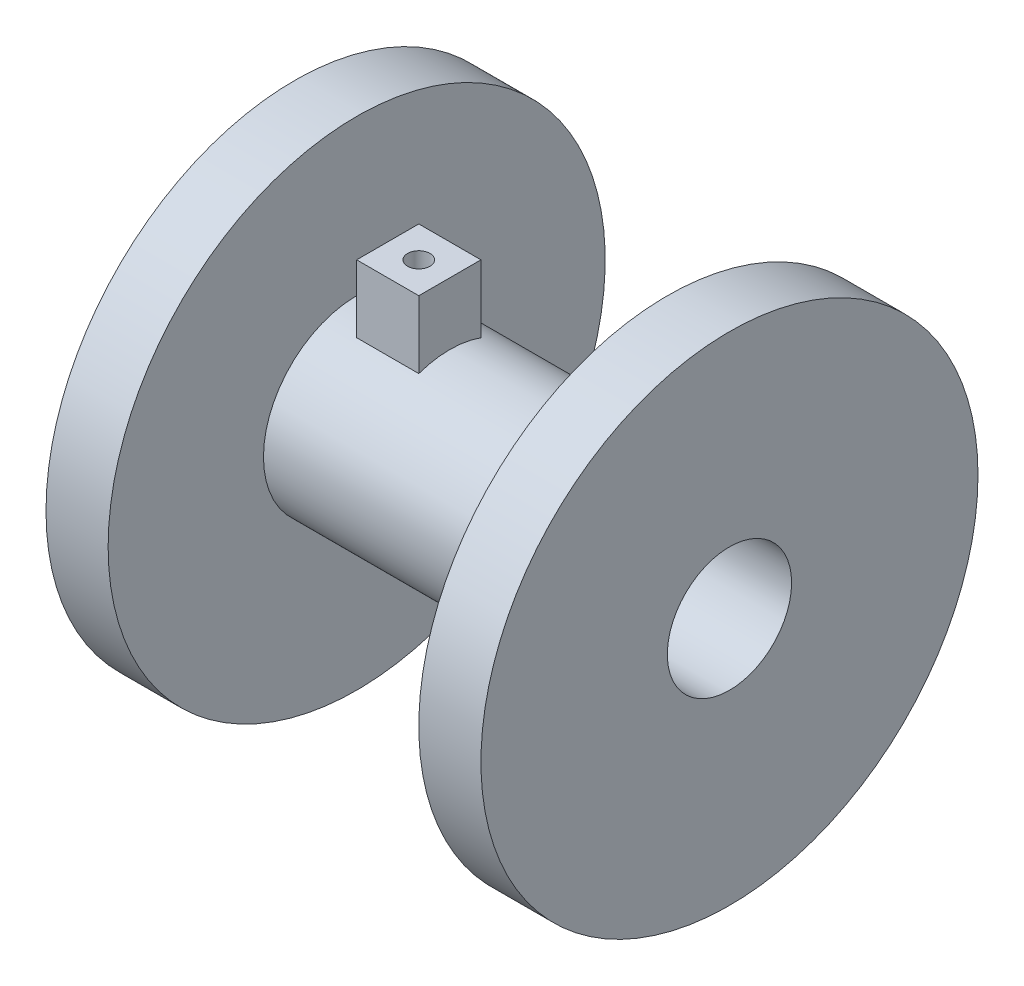
SolidWorks part; units mm, degrees
material "ABS PC"
ref_plane "Front Plane" through (0, 0, 0) normal (0, 0, 1) x (1, 0, 0)
ref_plane "Top Plane" through (0, 0, 0) normal (0, 1, 0) x (1, 0, 0)
ref_plane "Right Plane" through (0, 0, 0) normal (1, 0, 0) x (0, 0, -1)
sketch "Sketch1" plane through (0, 0, 0) normal (1, 0, 0) x (0, 0, -1)
  circle A0 centre (0, 0) radius 12.7
  circle A1 centre (0, 0) radius 19.05
  dimension "D1" = 25.4
  dimension "D2" = 38.1
extrude "Boss-Extrude1" add sketch "Sketch1" along normal mid plane 88.9
sketch "Sketch2" plane through (44.45, 0, 0) normal (1, 0, 0) x (0, 0, -1)
  circle A0 centre (0, 0) radius 50.8
  circle A1 centre (0, 0) radius 12.7 construction
  circle A2 centre (0, 0) radius 12.7
  dimension "D1" = 101.6
extrude "Boss-Extrude2" add sketch "Sketch2" against normal blind 12.7
sketch "Sketch3" plane through (-44.45, 0, 0) normal (-1, 0, 0) x (0, 0, 1)
  circle A0 centre (0, 0) radius 50.8
  circle A1 centre (0, 0) radius 12.7 construction
  circle A2 centre (0, 0) radius 12.7
  dimension "D1" = 101.6
extrude "Boss-Extrude3" add sketch "Sketch3" against normal blind 12.7
sketch "Sketch4" plane through (0, 0, 0) normal (0, 1, 0) x (1, 0, 0)
  line L0 (-44.45, 50.8) -> (-44.45, -50.8) construction
  line L1 (-25.4, -6.35) -> (-12.7, -6.35)
  line L2 (-25.4, -6.35) -> (-25.4, 6.35)
  line L3 (-25.4, 6.35) -> (-12.7, 6.35)
  line L4 (-12.7, -6.35) -> (-12.7, 6.35)
  line L5 (-25.4, -6.35) -> (-12.7, 6.35) construction
  line L6 (-25.4, 6.35) -> (-12.7, -6.35) construction
  circle A0 centre (-19.05, 0) radius 2.286
  point P0 (-19.05, 0)
  dimension "D3" = 4.572
  dimension "D1" = 12.7
  dimension "D2" = 25.4
extrude "Boss-Extrude4" add sketch "Sketch4" against normal up to next from offset 31.75
